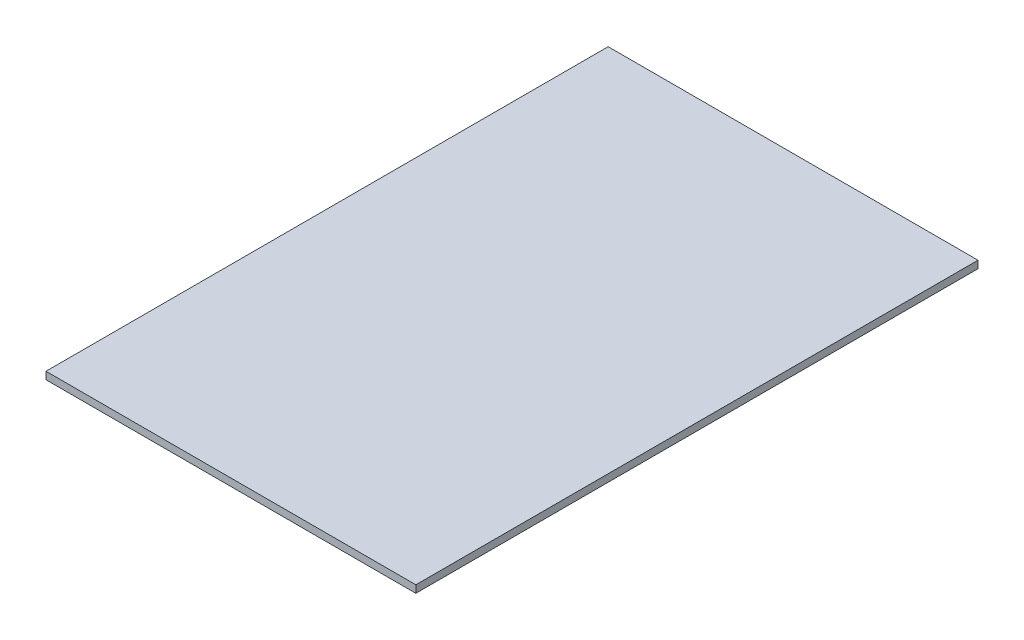
SolidWorks part; units mm, degrees
ref_plane "Front Plane" through (0, 0, 0) normal (0, 0, 1) x (1, 0, 0)
ref_plane "Top Plane" through (0, 0, 0) normal (0, 1, 0) x (1, 0, 0)
ref_plane "Right Plane" through (0, 0, 0) normal (1, 0, 0) x (0, 0, -1)
sketch "Sketch1" plane through (0, 0, 0) normal (0, 1, 0) x (1, 0, 0)
  line L1 (-158.75, -241.3) -> (158.75, -241.3)
  line L2 (-158.75, -241.3) -> (-158.75, 241.3)
  line L3 (-158.75, 241.3) -> (158.75, 241.3)
  line L4 (158.75, -241.3) -> (158.75, 241.3)
  line L5 (-158.75, -241.3) -> (158.75, 241.3) construction
  line L6 (-158.75, 241.3) -> (158.75, -241.3) construction
  point P0 (0, 0)
  dimension "D1" = 317.5
  dimension "D2" = 482.6
extrude "Boss-Extrude1" add sketch "Sketch1" along normal blind 6.35
